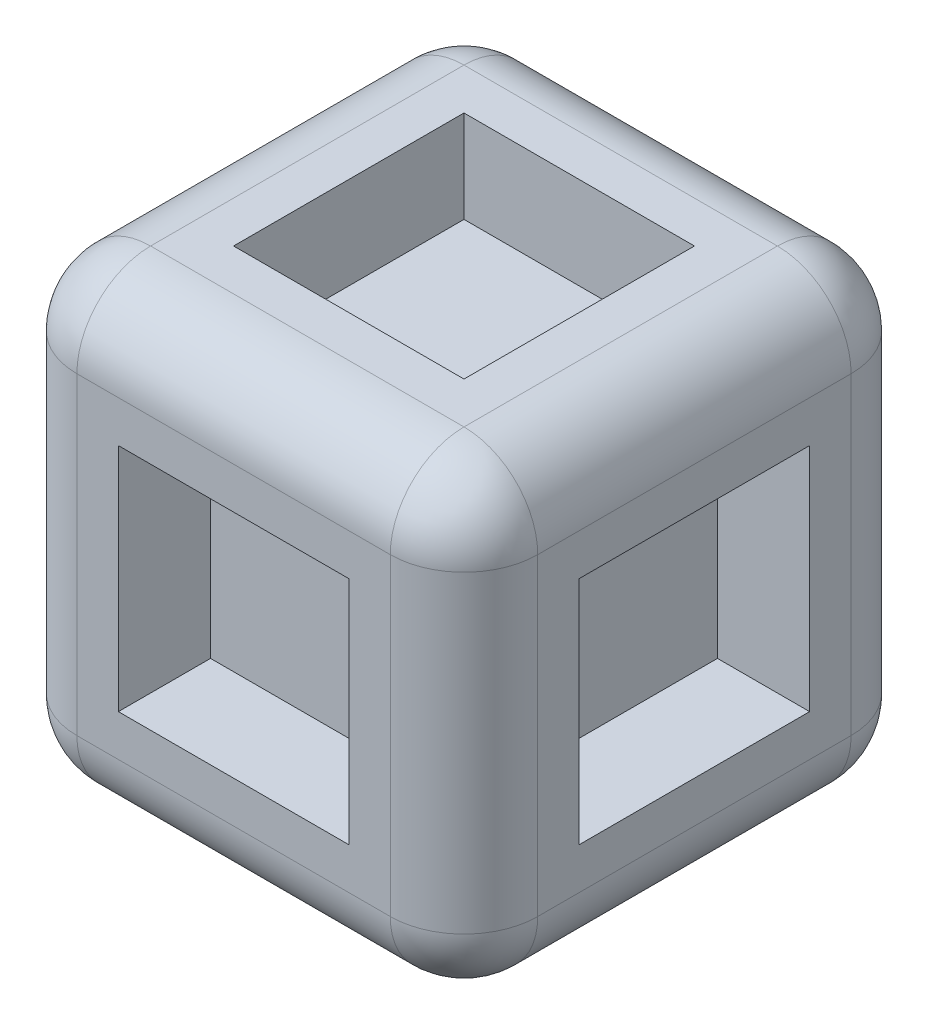
SolidWorks part; units mm, degrees
material "Plain Carbon Steel"
ref_plane "Front Plane" through (0, 0, 0) normal (0, 0, 1) x (1, 0, 0)
ref_plane "Top Plane" through (0, 0, 0) normal (0, 1, 0) x (1, 0, 0)
ref_plane "Right Plane" through (0, 0, 0) normal (1, 0, 0) x (0, 0, -1)
sketch "Sketch1" plane through (0, 0, 0) normal (0, 0, 1) x (1, 0, 0)
  line L0 (-6.6026, 0) -> (7.8365, 0) construction
  line L1 (-12.5, 12.5) -> (12.5, 12.5)
  line L2 (-12.5, 12.5) -> (-12.5, -12.5)
  line L3 (-12.5, -12.5) -> (12.5, -12.5)
  line L4 (12.5, 12.5) -> (12.5, -12.5)
  line L5 (-12.5, 12.5) -> (12.5, -12.5) construction
  line L6 (-12.5, -12.5) -> (12.5, 12.5) construction
  line L7 (-6.25, 6.25) -> (6.25, 6.25)
  line L8 (-6.25, 6.25) -> (-6.25, -6.25)
  line L9 (-6.25, -6.25) -> (6.25, -6.25)
  line L10 (6.25, 6.25) -> (6.25, -6.25)
  line L11 (-6.25, 6.25) -> (6.25, -6.25) construction
  line L12 (-6.25, -6.25) -> (6.25, 6.25) construction
  line L13 (0, 5.4728) -> (0, -6.8349) construction
  point P0 (0, 0)
  point P6 (0, 0)
  point P15 (-12.5, 0)
  dimension "D1" = 25
  dimension "D2" = 12.5
  dimension "D3" = 25
  dimension "D4" = 12.5
extrude "Boss-Extrude1" add sketch "Sketch1" along normal mid plane 25 contours L4 L1 L2 L3 L7 L10 L9 L8 | L10 L7 L8 L9
sketch "Sketch2" plane through (0, 0, -12.5) normal (0, 0, -1) x (-1, 0, 0)
  line L1 (-6.25, 6.25) -> (6.25, 6.25)
  line L2 (-6.25, 6.25) -> (-6.25, -6.25)
  line L3 (-6.25, -6.25) -> (6.25, -6.25)
  line L4 (6.25, 6.25) -> (6.25, -6.25)
  line L5 (-6.25, 6.25) -> (6.25, -6.25) construction
  line L6 (-6.25, -6.25) -> (6.25, 6.25) construction
  point P0 (0, 0)
  dimension "D2" = 12.5
  dimension "D1" = 12.5
extrude "Cut-Extrude1" cut sketch "Sketch2" against normal blind 5
mirror "Mirror1" about plane through (0, 0, 0) normal (0, 0, 1) of "Cut-Extrude1"
sketch "Sketch3" plane through (0, 12.5, 0) normal (0, 1, 0) x (1, 0, 0)
  line L1 (-6.25, 6.25) -> (6.25, 6.25)
  line L2 (-6.25, 6.25) -> (-6.25, -6.25)
  line L3 (-6.25, -6.25) -> (6.25, -6.25)
  line L4 (6.25, 6.25) -> (6.25, -6.25)
  line L5 (-6.25, 6.25) -> (6.25, -6.25) construction
  line L6 (-6.25, -6.25) -> (6.25, 6.25) construction
  point P0 (0, 0)
  dimension "D2" = 12.5
  dimension "D1" = 12.5
extrude "Cut-Extrude2" cut sketch "Sketch3" against normal blind 5
sketch "Sketch4" plane through (12.5, 0, 0) normal (1, 0, 0) x (0, 0, -1)
  line L1 (-6.25, 6.25) -> (6.25, 6.25)
  line L2 (-6.25, 6.25) -> (-6.25, -6.25)
  line L3 (-6.25, -6.25) -> (6.25, -6.25)
  line L4 (6.25, 6.25) -> (6.25, -6.25)
  line L5 (-6.25, 6.25) -> (6.25, -6.25) construction
  line L6 (-6.25, -6.25) -> (6.25, 6.25) construction
  point P0 (0, 0)
  dimension "D2" = 12.5
  dimension "D1" = 12.5
extrude "Cut-Extrude3" cut sketch "Sketch4" against normal blind 5
mirror "Mirror2" about plane through (0, 0, 0) normal (1, 0, 0) of "Cut-Extrude3"
mirror "Mirror3" about plane through (0, 0, 0) normal (0, 1, 0) of "Cut-Extrude2"
fillet "Fillet1" radius 4 12 edges at (-12.5, 12.5, 0) (-12.5, 0, 12.5) (0, 12.5, 12.5) (-12.5, -12.5, 0) (0, -12.5, 12.5) (12.5, -12.5, 0) (12.5, 0, 12.5) (12.5, 12.5, 0) (0, 12.5, -12.5) (-12.5, 0, -12.5) (0, -12.5, -12.5) (12.5, 0, -12.5)
equation "\"A\"= 25"
equation "\"D1@Sketch1\"=\"A\""
equation "\"D2@Sketch1\"=\"A\"/2"
equation "\"D3@Sketch1\"=\"A\""
equation "\"D4@Sketch1\"=\"A\"/2"
equation "\"D1@Sketch2\"=\"A\"/2"
equation "\"D2@Sketch2\"=\"A\"/2"
equation "\"B\"= 5"
equation "\"D1@Cut-Extrude1\"=\"B\""
equation "\"D1@Sketch3\"=\"A\"/2"
equation "\"D2@Sketch3\"=\"A\"/2"
equation "\"D1@Cut-Extrude2\"=\"B\""
equation "\"D1@Sketch4\"=\"A\"/2"
equation "\"D2@Sketch4\"=\"A\"/2"
equation "\"D1@Cut-Extrude3\"=\"B\""
equation "\"c\"= 4"
equation "\"D1@Fillet1\"=\"c\""
equation "\"D1@Boss-Extrude1\"=\"A\""
